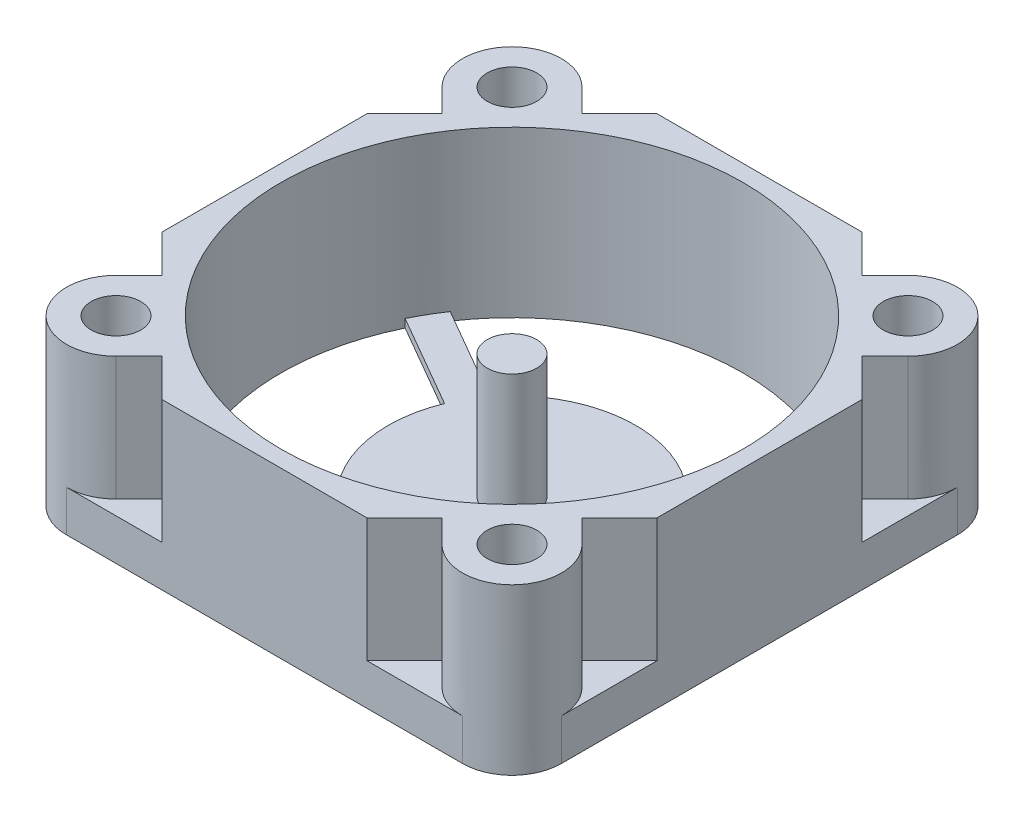
SolidWorks part; units mm, degrees
material "ABS PC"
ref_plane "Front Plane" through (0, 0, 0) normal (0, 0, 1) x (1, 0, 0)
ref_plane "Top Plane" through (0, 0, 0) normal (0, 1, 0) x (1, 0, 0)
ref_plane "Right Plane" through (0, 0, 0) normal (1, 0, 0) x (0, 0, -1)
sketch "Sketch1" plane through (0, 0, 0) normal (0, 1, 0) x (1, 0, 0)
  line L1 (-12, 15) -> (12, 15)
  line L2 (-15, 12) -> (-15, -12)
  line L3 (-12, -15) -> (12, -15)
  line L4 (15, 12) -> (15, -12)
  line L5 (-15, 15) -> (15, -15) construction
  line L6 (-15, -15) -> (15, 15) construction
  arc A0 (12, 15) -> (15, 12) centre (12, 12) cw
  arc A1 (15, -12) -> (12, -15) centre (12, -12) cw
  arc A2 (-12, -15) -> (-15, -12) centre (-12, -12) cw
  arc A3 (-12, 15) -> (-15, 12) centre (-12, 12) ccw
  circle A4 centre (-12, -12) radius 1.5
  circle A5 centre (-12, 12) radius 1.5
  circle A6 centre (12, 12) radius 1.5
  circle A7 centre (12, -12) radius 1.5
  point P0 (0, 0)
  dimension "D3" = 3
  dimension "D4" = 3
  dimension "D5" = 3
  dimension "D6" = 3
  dimension "D7" = 3
  dimension "D1" = 30
  dimension "D2" = 30
extrude "Boss-Extrude1" add sketch "Sketch1" along normal blind 10
sketch "Sketch2" plane through (0, 10, 0) normal (0, 1, 0) x (1, 0, 0)
  circle A0 centre (0, 0) radius 14
  dimension "D1" = 28
extrude "Cut-Extrude1" cut sketch "Sketch2" against normal blind 9.5
sketch "Sketch3" plane through (0, 0, 0) normal (0, -1, 0) x (1, 0, 0)
  line L0 (6.9372, -2.8505) -> (12.5934, -6.1161)
  line L1 (5.9372, -4.5825) -> (11.5934, -7.8481)
  line L3 (-1, 7.433) -> (-1, 13.9642)
  line L5 (1, 7.433) -> (1, 13.9642)
  line L6 (-5.9372, -4.5825) -> (-11.5934, -7.8481)
  line L7 (-6.9372, -2.8505) -> (-12.5934, -6.1161)
  arc A0 (-1, 7.433) -> (-6.9372, -2.8505) centre (0, 0) ccw
  arc A1 (-1, 13.9642) -> (-12.5934, -6.1161) centre (0, 0) ccw
  arc A2 (-5.9372, -4.5825) -> (5.9372, -4.5825) centre (0, 0) ccw
  arc A3 (-11.5934, -7.8481) -> (11.5934, -7.8481) centre (0, 0) ccw
  arc A4 (6.9372, -2.8505) -> (1, 7.433) centre (0, 0) ccw
  arc A5 (12.5934, -6.1161) -> (1, 13.9642) centre (0, 0) ccw
  point P6 (0, 10.75)
  point P17 (0, 0)
  dimension "D1" = 15
  dimension "D2" = 2
  dimension "D3" = 3
extrude "Cut-Extrude2" cut sketch "Sketch3" against normal blind 10
sketch "Sketch4" plane through (0, 0.5, 0) normal (0, 1, 0) x (1, 0, 0)
  circle A0 centre (0, 0) radius 1.5
  dimension "D1" = 3
extrude "Boss-Extrude2" add sketch "Sketch4" along normal blind 7.5
sketch "Sketch5" plane through (0, 10, 0) normal (0, 1, 0) x (1, 0, 0)
  line L8 (-6.2132, 15) -> (-8.4853, 12.7279)
  line L9 (-9.8787, 14.1213) -> (-8.4853, 12.7279)
  line L10 (-14.1213, 9.8787) -> (-12.7279, 8.4853)
  line L11 (-15, 12) -> (-15, 6.2132)
  line L12 (-12, 15) -> (-6.2132, 15)
  line L13 (-12.7279, 8.4853) -> (-15, 6.2132)
  line L14 (15, 6.2132) -> (12.7279, 8.4853)
  line L15 (14.1213, 9.8787) -> (12.7279, 8.4853)
  line L16 (9.8787, 14.1213) -> (8.4853, 12.7279)
  line L17 (12, 15) -> (6.2132, 15)
  line L18 (15, 12) -> (15, 6.2132)
  line L19 (8.4853, 12.7279) -> (6.2132, 15)
  line L20 (6.2132, -15) -> (8.4853, -12.7279)
  line L21 (9.8787, -14.1213) -> (8.4853, -12.7279)
  line L22 (14.1213, -9.8787) -> (12.7279, -8.4853)
  line L23 (15, -12) -> (15, -6.2132)
  line L24 (12, -15) -> (6.2132, -15)
  line L25 (12.7279, -8.4853) -> (15, -6.2132)
  line L26 (-15, -6.2132) -> (-12.7279, -8.4853)
  line L27 (-14.1213, -9.8787) -> (-12.7279, -8.4853)
  line L28 (-9.8787, -14.1213) -> (-8.4853, -12.7279)
  line L29 (-12, -15) -> (-6.2132, -15)
  line L30 (-15, -12) -> (-15, -6.2132)
  line L31 (-8.4853, -12.7279) -> (-6.2132, -15)
  arc A0 (14.1213, 9.8787) -> (15, 12) centre (12, 12) ccw
  arc A1 (-9.8787, 14.1213) -> (-12, 15) centre (-12, 12) ccw
  arc A2 (-12, 15) -> (-15, 12) centre (-12, 12) ccw construction
  arc A3 (-15, 12) -> (-14.1213, 9.8787) centre (-12, 12) ccw
  arc A4 (12, 15) -> (9.8787, 14.1213) centre (12, 12) ccw
  arc A5 (9.8787, -14.1213) -> (12, -15) centre (12, -12) ccw
  arc A6 (15, -12) -> (14.1213, -9.8787) centre (12, -12) ccw
  arc A7 (-14.1213, -9.8787) -> (-15, -12) centre (-12, -12) ccw
  arc A8 (-12, -15) -> (-9.8787, -14.1213) centre (-12, -12) ccw
  point P46 (0, 0)
  dimension "D1" = 4
extrude "Cut-Extrude3" cut sketch "Sketch5" against normal blind 7.5
